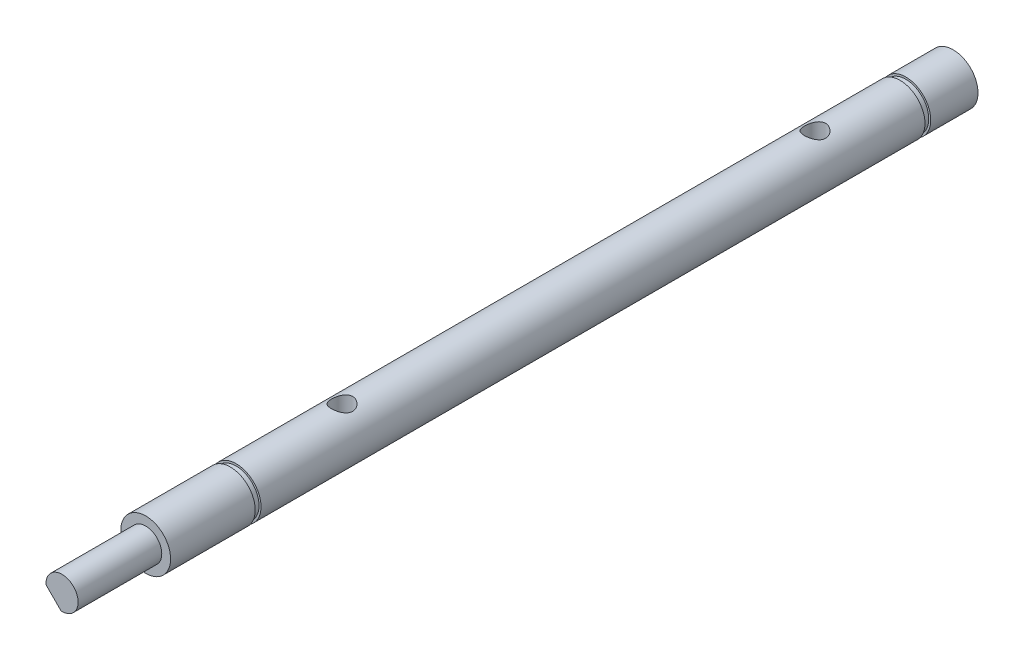
SolidWorks part; units mm, degrees
ref_plane "Front Plane" through (0, 0, 0) normal (0, 0, 1) x (1, 0, 0)
ref_plane "Top Plane" through (0, 0, 0) normal (0, 1, 0) x (1, 0, 0)
ref_plane "Right Plane" through (0, 0, 0) normal (1, 0, 0) x (0, 0, -1)
sketch "Sketch1" plane through (0, 0, 0) normal (0, 1, 0) x (1, 0, 0)
  line L0 (-37.5831, -1.5875) -> (-37.5831, -13.843) construction
  line L2 (-11.3881, -3.175) -> (-59.6781, -3.175) construction
  line L4 (-38.7081, 7.62) -> (-38.4541, 7.62) construction
  line L5 (-38.4541, 7.62) -> (-38.4541, 8.3566) construction
  line L6 (-38.7081, 8.3566) -> (-38.4541, 8.3566) construction
  line L7 (-30.7706, 26.6211) -> (-30.7706, 17.0961) construction
  line L8 (-30.7706, 17.0961) -> (-40.2956, 17.0961) construction
  line L9 (-40.2956, 26.6211) -> (-40.2956, 17.0961) construction
  line L10 (-30.7706, 26.6211) -> (-40.2956, 26.6211) construction
  line L11 (-35.5331, -1.5875) -> (-35.5331, 99.7956) construction
  line L12 (-47.4394, 77.4211) -> (-23.6269, 77.4211) construction
  line L13 (-30.7706, 77.4211) -> (-30.7706, 86.9461) construction
  line L14 (-30.7706, 86.9461) -> (-40.2956, 86.9461) construction
  line L15 (-40.2956, 77.4211) -> (-40.2956, 86.9461) construction
  line L16 (-32.3581, 99.7956) -> (-38.7081, 99.7956) construction
  line L17 (-38.7081, -1.5875) -> (-38.7081, 99.7956) construction
  line L18 (-38.7081, 93.7694) -> (-38.4541, 93.7694) construction
  line L19 (-38.4541, 93.7694) -> (-38.4541, 93.0328) construction
  line L20 (-38.7081, 93.0328) -> (-38.4541, 93.0328) construction
  line L21 (-37.5831, -3.175) -> (-37.5831, -13.843)
  line L22 (-35.5331, 86.9461) -> (-35.5331, 77.4211) construction
  line L23 (-37.5831, -3.175) -> (-38.7081, -3.175)
  line L25 (-38.7081, 7.62) -> (-38.4541, 7.62)
  line L26 (-38.4541, 7.62) -> (-38.4541, 8.3566)
  line L27 (-38.7081, 8.3566) -> (-38.4541, 8.3566)
  line L28 (-30.7706, 26.6211) -> (-30.7706, 17.0961)
  line L29 (-30.7706, 17.0961) -> (-40.2956, 17.0961)
  line L30 (-40.2956, 26.6211) -> (-40.2956, 17.0961)
  line L31 (-30.7706, 26.6211) -> (-40.2956, 26.6211)
  line L32 (-35.5331, -13.843) -> (-35.5331, 99.7956)
  line L33 (-40.2956, 77.4211) -> (-30.7706, 77.4211)
  line L34 (-30.7706, 77.4211) -> (-30.7706, 86.9461)
  line L35 (-30.7706, 86.9461) -> (-40.2956, 86.9461)
  line L36 (-40.2956, 77.4211) -> (-40.2956, 86.9461)
  line L37 (-35.5331, 99.7956) -> (-38.7081, 99.7956)
  line L38 (-38.7081, -3.175) -> (-38.7081, 7.62)
  line L39 (-38.7081, 93.7694) -> (-38.4541, 93.7694)
  line L40 (-38.4541, 93.7694) -> (-38.4541, 93.0328)
  line L41 (-38.7081, 93.0328) -> (-38.4541, 93.0328)
  line L42 (-33.4831, -13.843) -> (-37.5831, -13.843) construction
  line L43 (-35.5331, -13.843) -> (-37.5831, -13.843)
  line L44 (-38.7081, 93.7694) -> (-38.7081, 99.7956)
  line L45 (-38.7081, 8.3566) -> (-38.7081, 93.0328)
  line L47 (-35.5331, 26.6211) -> (-35.5331, 17.0961) construction
  point P28 (-35.5331, 82.1836)
  point P31 (-35.5331, 21.8586)
revolve "Revolve1" add sketch "Sketch1" angle 360 about L32
ref_plane "Plane1" through (0, -3.175, 0) normal (0, -1, 0) x (-1, 0, 0)
hole_wizard "#6-32 Tapped Hole1" positions "Sketch2" profile "Sketch3" tap size "#6-32" standard "ANSI Inch"
sketch "Sketch2" plane through (0, -3.175, 0) normal (0, -1, 0) x (-1, 0, 0)
  point P0 (35.5331, 82.1836)
  point P2 (35.5331, 21.8586)
sketch "Sketch3" plane through (-35.5331, -3.175, -82.1836) normal (1, 0, 0) x (0, 0, -1)
  line L0 (0, 0) -> (0, 10.2107)
  line L1 (0, 10.2107) -> (1.3525, 9.398)
  line L2 (1.3525, 9.398) -> (1.3525, 0)
  line L5 (1.3525, 0) -> (0, 0)
  line L10 (0, 10.2107) -> (-1.3525, 9.398) construction
  line L11 (0, -6.35) -> (0, 107.95) construction
  dimension "Tap Drill Dia." = 2.7051
  dimension "Tap Drill Depth" = 9.398
  dimension "Drill Angle" = 118
cosmetic thread "Hole Thread1" parameters "D1"=0, "D2"=3.7051
cosmetic thread "Hole Thread2" parameters "D1"=0, "D2"=3.7051
sketch "Sketch4" plane through (0, 0, 13.843) normal (0, 0, 1) x (1, 0, 0)
  line L0 (-35.6615, -2.046) -> (-37.5791, -0.1284)
  line L1 (-35.5331, 0) -> (-37.5831, 0) construction
  circle A1 centre (-35.5331, 0) radius 2.05
  circle A2 centre (-35.5331, 0) radius 2.05
  circle M3 centre (-35.5331, 0) radius 2.05
  dimension "D3" = 4.1
  dimension "D2" = 1.5375
  dimension "D4" = 45
  dimension "D1" = 0
extrude "Cut-Extrude1" cut sketch "Sketch4" against normal blind 6.35 contours L0 M3
equation "\"D2@Sketch4\"=\"D3@Sketch4\"/2*3/4"
